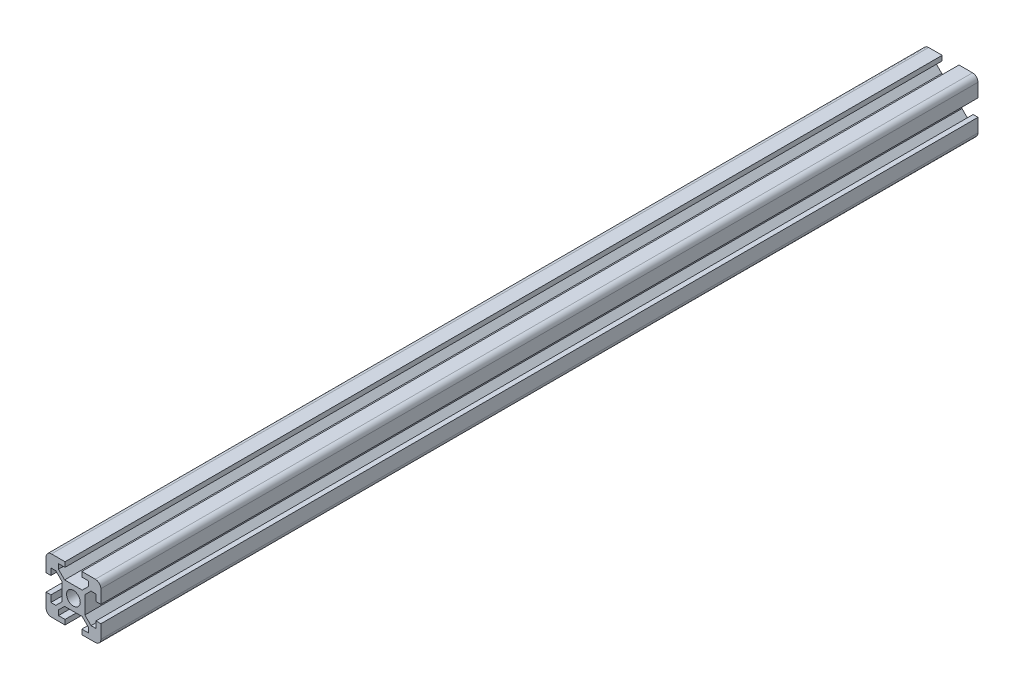
SolidWorks part; units mm, degrees
material "1060 Alloy"
ref_plane "Front Plane" through (0, 0, 0) normal (0, 0, 1) x (1, 0, 0)
ref_plane "Top Plane" through (0, 0, 0) normal (0, 1, 0) x (1, 0, 0)
ref_plane "Right Plane" through (0, 0, 0) normal (1, 0, 0) x (0, 0, -1)
sketch "Sketch1" plane through (0, 0, 0) normal (0, 0, 1) x (1, 0, 0)
  line L0 (-5.46, -6.42) -> (-3.215, -4.175)
  line L1 (-10, -10) -> (-3.06, -10)
  line L2 (-10, -10) -> (-10, -3.06)
  line L3 (-10, 10) -> (-3.06, 10)
  line L4 (10, -10) -> (10, -3.06)
  line L5 (-10, -10) -> (10, 10) construction
  line L6 (-10, 10) -> (10, -10) construction
  line L7 (-3.215, -4.175) -> (3.215, -4.175)
  line L8 (-4.175, -3.215) -> (-4.175, 3.215)
  line L9 (-3.215, 4.175) -> (3.215, 4.175)
  line L10 (4.175, -3.215) -> (4.175, 3.215)
  line L11 (-4.175, -4.175) -> (4.175, 4.175) construction
  line L12 (-4.175, 4.175) -> (4.175, -4.175) construction
  line L13 (-5.46, 6.42) -> (-5.46, 8.22)
  line L14 (-5.46, 8.22) -> (-3.06, 8.22)
  line L15 (-3.06, 8.22) -> (-3.06, 10)
  line L16 (-6.42, -5.46) -> (-4.175, -3.215)
  line L17 (5.46, 6.42) -> (5.46, 8.22)
  line L18 (5.46, 8.22) -> (3.06, 8.22)
  line L19 (3.06, 8.22) -> (3.06, 10)
  line L20 (-5.46, 6.42) -> (-3.215, 4.175)
  line L21 (6.42, 5.46) -> (8.22, 5.46)
  line L22 (8.22, 5.46) -> (8.22, 3.06)
  line L23 (8.22, 3.06) -> (10, 3.06)
  line L24 (8.22, -5.46) -> (6.42, -5.46)
  line L25 (-6.42, 5.46) -> (-4.175, 3.215)
  line L26 (8.22, -5.46) -> (8.22, -3.06)
  line L27 (8.22, -3.06) -> (10, -3.06)
  line L28 (5.46, 6.42) -> (3.215, 4.175)
  line L29 (5.46, -6.42) -> (5.46, -8.22)
  line L30 (5.46, -8.22) -> (3.06, -8.22)
  line L31 (3.06, -8.22) -> (3.06, -10)
  line L32 (6.42, 5.46) -> (4.175, 3.215)
  line L33 (-6.42, 5.46) -> (-8.22, 5.46)
  line L34 (-8.22, 5.46) -> (-8.22, 3.06)
  line L35 (-8.22, 3.06) -> (-10, 3.06)
  line L36 (6.42, -5.46) -> (4.175, -3.215)
  line L37 (-6.42, -5.46) -> (-8.22, -5.46)
  line L38 (-8.22, -5.46) -> (-8.22, -3.06)
  line L39 (-8.22, -3.06) -> (-10, -3.06)
  line L40 (5.46, -6.42) -> (3.215, -4.175)
  line L41 (-5.46, -6.42) -> (-5.46, -8.22)
  line L42 (-5.46, -8.22) -> (-3.06, -8.22)
  line L43 (-3.06, -8.22) -> (-3.06, -10)
  line L44 (-10, 3.06) -> (-10, 10)
  line L45 (3.06, 10) -> (10, 10)
  line L46 (10, 3.06) -> (10, 10)
  line L47 (3.06, -10) -> (10, -10)
  circle A0 centre (0, 0) radius 2.5
  point P0 (0, 0)
  dimension "D3" = 5
  dimension "D1" = 20
  dimension "D2" = 20
  dimension "D4" = 8.35
  dimension "D5" = 8.35
  dimension "D6" = 6.94
  dimension "D7" = 1.78
  dimension "D8" = 2.4
  dimension "D9" = 1.8
extrude "Boss-Extrude1" add sketch "Sketch1" along normal blind 320
fillet "Fillet1" radius 2 4 edges at (-10, -10, 160) (10, -10, 160) (-10, 10, 160) (10, 10, 160)
ref_plane "Plane1" through (0, 0, 50) normal (0, 0, 1) x (1, 0, 0)
